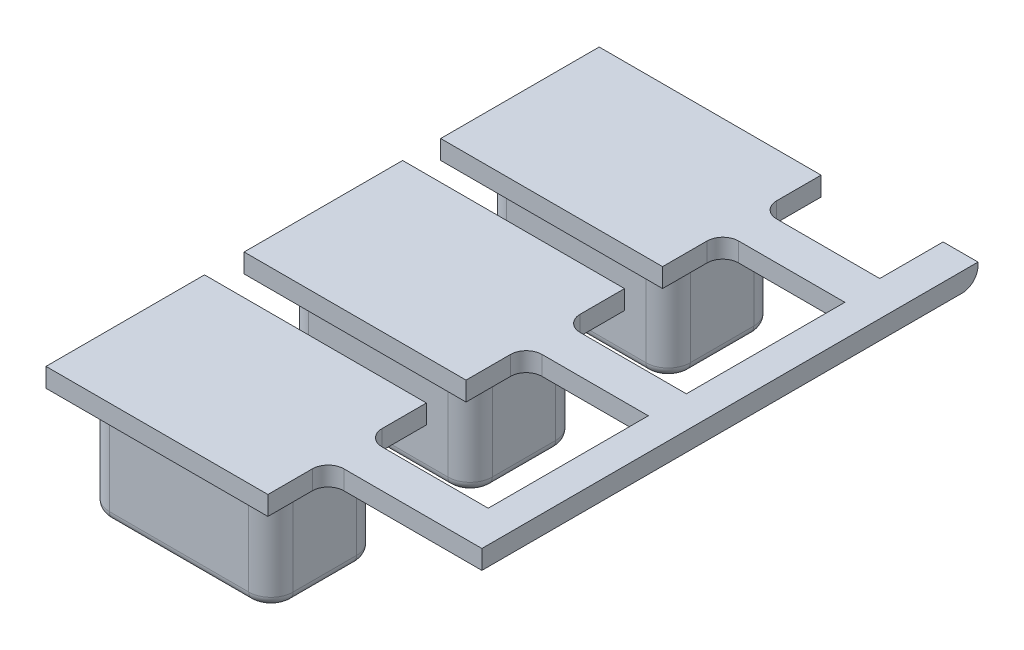
SolidWorks part; units mm, degrees
ref_plane "前视基准面" through (0, 0, 0) normal (0, 0, 1) x (1, 0, 0)
ref_plane "上视基准面" through (0, 0, 0) normal (0, 1, 0) x (1, 0, 0)
ref_plane "右视基准面" through (0, 0, 0) normal (1, 0, 0) x (0, 0, -1)
sketch "草图1" plane through (0, 0, 0) normal (0, 1, 0) x (1, 0, 0)
  line L0 (-2.2, 1.2454) -> (2.2, 1.2454)
  line L5 (-2.2, 7.5287) -> (2.2, 7.5287)
  line L6 (2.9, 6.8287) -> (2.9, 4.8287)
  line L7 (2.9, 0.5454) -> (2.9, -1.4546)
  line L8 (-2.2, -2.1546) -> (2.2, -2.1546)
  line L9 (-2.9, 0.5454) -> (-2.9, -1.4546)
  line L10 (-2.2, 4.1287) -> (2.2, 4.1287)
  line L11 (-2.9, 6.8287) -> (-2.9, 4.8287)
  line L12 (-2.2, 13.7759) -> (2.2, 13.7759)
  line L13 (2.9, 13.0759) -> (2.9, 11.0759)
  line L14 (-2.2, 10.3759) -> (2.2, 10.3759)
  line L15 (-2.9, 13.0759) -> (-2.9, 11.0759)
  arc A4 (2.2, 1.2454) -> (2.9, 0.5454) centre (2.2, 0.5454) cw
  arc A5 (2.2, -2.1546) -> (2.9, -1.4546) centre (2.2, -1.4546) ccw
  arc A6 (-2.9, -1.4546) -> (-2.2, -2.1546) centre (-2.2, -1.4546) ccw
  arc A7 (-2.2, 1.2454) -> (-2.9, 0.5454) centre (-2.2, 0.5454) ccw
  arc A8 (2.2, 7.5287) -> (2.9, 6.8287) centre (2.2, 6.8287) cw
  arc A9 (2.2, 4.1287) -> (2.9, 4.8287) centre (2.2, 4.8287) ccw
  arc A10 (-2.9, 4.8287) -> (-2.2, 4.1287) centre (-2.2, 4.8287) ccw
  arc A11 (-2.2, 7.5287) -> (-2.9, 6.8287) centre (-2.2, 6.8287) ccw
  arc A12 (2.2, 13.7759) -> (2.9, 13.0759) centre (2.2, 13.0759) cw
  arc A13 (2.2, 10.3759) -> (2.9, 11.0759) centre (2.2, 11.0759) ccw
  arc A14 (-2.9, 11.0759) -> (-2.2, 10.3759) centre (-2.2, 11.0759) ccw
  arc A15 (-2.2, 13.7759) -> (-2.9, 13.0759) centre (-2.2, 13.0759) ccw
  point P0 (0, 0)
  point P1 (-0.0497, 5.8287)
  point P15 (-0.0145, 11.6491)
  point P40 (0, 0)
  point P41 (0, 0)
  point P42 (0, 0)
  point P43 (0, 0)
  point P44 (0, 0)
  point P45 (0, 0)
  point P46 (0, 0)
  point P47 (0, 0)
  dimension "D1" = 3.4
  dimension "D2" = 5.8
extrude "凸台-拉伸1" add sketch "草图1" along normal blind 4
sketch "草图2" plane through (0, 4, 0) normal (0, 1, 0) x (1, 0, 0)
  line L1 (-3.4633, 14.5631) -> (3.5367, 14.5631)
  line L2 (-3.4633, 14.5631) -> (-3.4633, 9.5631)
  line L3 (-3.4633, 9.5631) -> (3.5367, 9.5631)
  line L4 (3.5367, 14.5631) -> (3.5367, 9.5631)
  line L5 (-3.4633, 8.3631) -> (3.5367, 8.3631)
  line L6 (-3.4633, 8.3631) -> (-3.4633, 3.3631)
  line L7 (-3.4633, 3.3631) -> (3.5367, 3.3631)
  line L8 (3.5367, 8.3631) -> (3.5367, 3.3631)
  line L9 (3.5367, 2.1131) -> (-3.4633, 2.1131)
  line L10 (3.5367, 2.1131) -> (3.5367, -2.8869)
  line L11 (3.5367, -2.8869) -> (-3.4633, -2.8869)
  line L12 (-3.4633, 2.1131) -> (-3.4633, -2.8869)
  point P12 (0, 0)
  dimension "D1" = 5
  dimension "D2" = 5
  dimension "D3" = 5
  dimension "D4" = 7
  dimension "D5" = 1.2
  dimension "D6" = 1.25
extrude "凸台-拉伸2" add sketch "草图2" against normal blind 0.6
sketch "草图3" plane through (0, 4, 0) normal (0, 1, 0) x (1, 0, 0)
  line L0 (3.5367, 9.5631) -> (3.5367, 14.5631) construction
  line L1 (3.5367, 12.6631) -> (8.3867, 12.6631)
  line L2 (3.5367, 12.6631) -> (3.5367, 11.4631)
  line L3 (3.5367, 11.4631) -> (8.3867, 11.4631)
  line L4 (8.3867, 12.6631) -> (8.3867, 11.4631)
  line L5 (3.5367, 3.3631) -> (3.5367, 8.3631) construction
  line L6 (3.5367, 6.4631) -> (8.3867, 6.4631)
  line L7 (3.5367, 6.4631) -> (3.5367, 5.2631)
  line L8 (3.5367, 5.2631) -> (8.3867, 5.2631)
  line L9 (8.3867, 6.4631) -> (8.3867, 5.2631)
  line L10 (3.5367, -2.8869) -> (3.5367, 2.1131) construction
  line L11 (3.5367, 0.2131) -> (8.3867, 0.2131)
  line L12 (3.5367, 0.2131) -> (3.5367, -0.9869)
  line L13 (3.5367, -0.9869) -> (8.3867, -0.9869)
  line L14 (8.3867, 0.2131) -> (8.3867, -0.9869)
  line L15 (-3.4633, 14.5631) -> (-3.4633, 9.5631) construction
  line L16 (-3.4633, 8.3631) -> (-3.4633, 3.3631) construction
  line L17 (-3.4633, 2.1131) -> (-3.4633, -2.8869) construction
  point P20 (-3.4633, 12.0631)
  point P21 (8.3867, 12.0631)
  point P24 (-3.4633, 5.8631)
  point P25 (8.3867, 5.8631)
  point P28 (-3.4633, -0.3869)
  point P29 (8.3867, -0.3869)
  dimension "D3" = 1.2
  dimension "D4" = 4.85
extrude "凸台-拉伸3" add sketch "草图3" against normal blind 0.6
sketch "草图4" plane through (0, 3.4, 0) normal (0, -1, 0) x (1, 0, 0)
  line L0 (3.5367, 0.9869) -> (8.3867, 0.9869) construction
  line L1 (8.3867, 0.9869) -> (7.3867, 0.9869)
  line L2 (8.3867, 0.9869) -> (8.3867, -12.6631)
  line L3 (8.3867, -12.6631) -> (7.3867, -12.6631)
  line L4 (7.3867, 0.9869) -> (7.3867, -12.6631)
  line L5 (8.3867, -12.6631) -> (3.5367, -12.6631) construction
  dimension "D1" = 1
extrude "凸台-拉伸4" add sketch "草图4" against normal blind 0.6
fillet "圆角1" radius 0.5 6 edges at (3.5367, 3.7, -12.6631) (3.5367, 3.7, -11.4631) (3.5367, 3.7, -5.2631) (3.5367, 3.7, -6.4631) (3.5367, 3.7, 0.9869) (3.5367, 3.7, -0.2131)
fillet "圆角2" radius 0.3 24 edges at (2.695, 0, -13.5709) (2.9, 0, -12.0759) (2.695, 0, -10.5809) (0, 0, -10.3759) (-2.695, 0, -10.5809) (-2.9, 0, -12.0759) (-2.695, 0, -13.5709) (2.695, 0, -7.3237) (2.9, 0, -5.8287) (2.695, 0, -4.3337) (0, 0, -4.1287) (-2.695, 0, -4.3337) (-2.9, 0, -5.8287) (-2.695, 0, -7.3237) (2.695, 0, -1.0404) (2.9, 0, 0.4546) (2.695, 0, 1.9496) (0, 0, 2.1546) (-2.695, 0, 1.9496) (-2.9, 0, 0.4546) (-2.695, 0, -1.0404) (0, 0, -13.7759) (0, 0, -7.5287) (0, 0, -1.2454)
sketch "草图5" plane through (0, 0, -12.6631) normal (0, 0, -1) x (-1, 0, 0)
  line L0 (-4.0367, 4) -> (-8.3867, 4) construction
  line L1 (-8.3867, 3.4) -> (-7.2867, 3.4)
  line L2 (-8.3867, 3.4) -> (-8.3867, 4)
  line L3 (-8.3867, 4) -> (-7.2867, 4)
  line L4 (-7.2867, 3.4) -> (-7.2867, 4)
  dimension "D1" = 1.1
extrude "凸台-拉伸5" add sketch "草图5" along normal blind 2
fillet "圆角3" radius 0.5 1 edges at (7.8367, 3.4, -14.6631)
